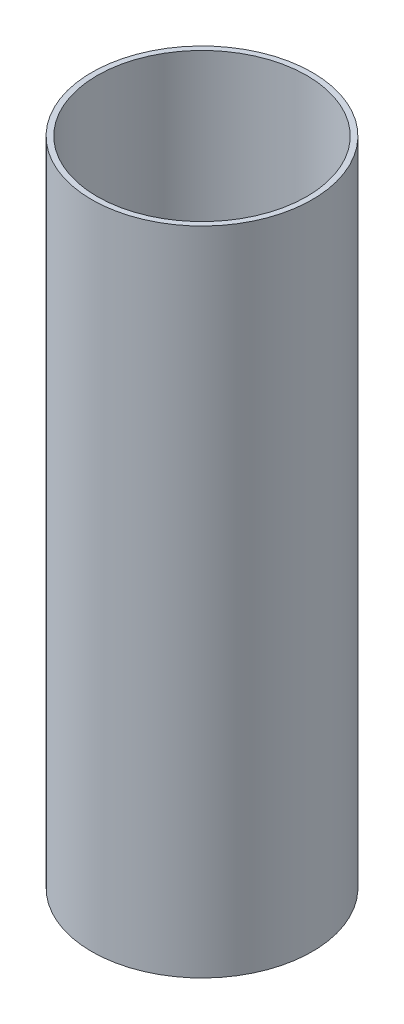
SolidWorks part; units mm, degrees
ref_plane "Front Plane" through (0, 0, 0) normal (0, 0, 1) x (1, 0, 0)
ref_plane "Top Plane" through (0, 0, 0) normal (0, 1, 0) x (1, 0, 0)
ref_plane "Right Plane" through (0, 0, 0) normal (1, 0, 0) x (0, 0, -1)
sketch "Sketch1" plane through (0, 0, 0) normal (0, 1, 0) x (1, 0, 0)
  circle A0 centre (0, 0) radius 25.4
  circle A1 centre (0, 0) radius 24.15
  dimension "D1" = 50.8
  dimension "D2" = 48.3
extrude "Boss-Extrude1" add sketch "Sketch1" along normal blind 150
